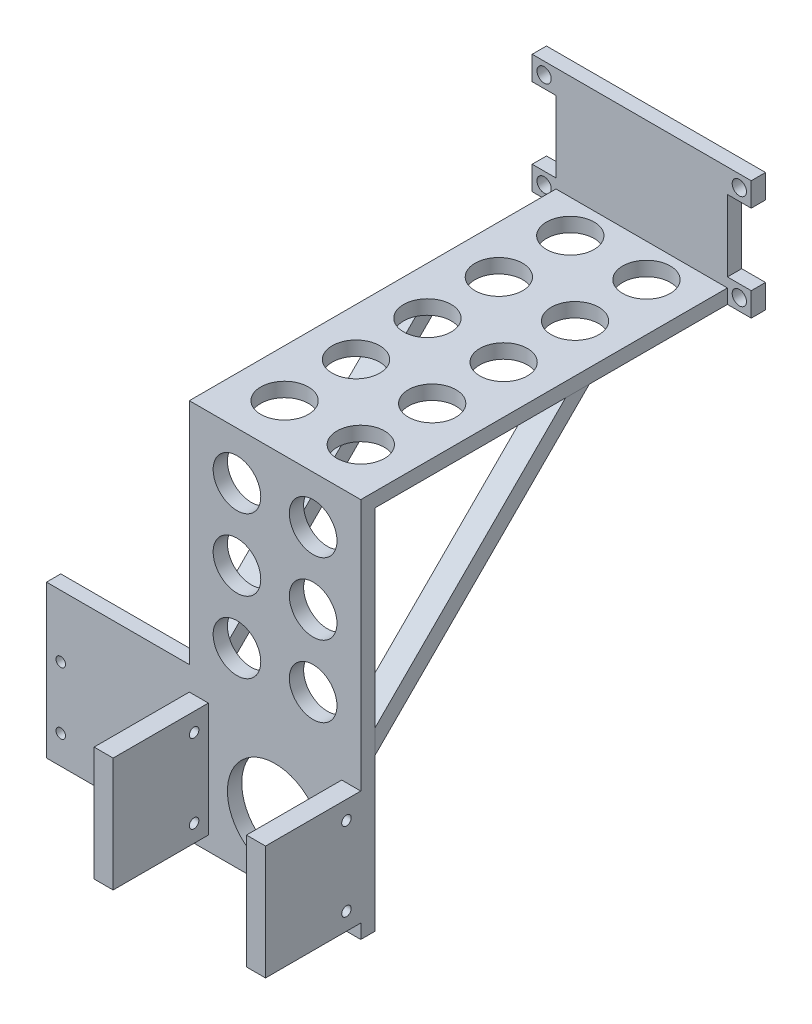
SolidWorks part; units mm, degrees
ref_plane "前视基准面" through (0, 0, 0) normal (0, 0, 1) x (1, 0, 0)
ref_plane "上视基准面" through (0, 0, 0) normal (0, 1, 0) x (1, 0, 0)
ref_plane "右视基准面" through (0, 0, 0) normal (1, 0, 0) x (0, 0, -1)
other "Configuration Table"
sketch "草图1" plane through (0, 0, 0) normal (0, 0, 1) x (1, 0, 0)
  line L1 (-18, 12.5) -> (18, 12.5)
  line L2 (-18, 12.5) -> (-18, -12.5)
  line L3 (-18, -12.5) -> (18, -12.5)
  line L4 (18, 12.5) -> (18, -12.5)
  line L5 (0, -12.5) -> (0, 12.5) construction
  line L6 (-18, 0) -> (18, 0) construction
  point P0 (0, 0)
  dimension "D1" = 25
  dimension "D2" = 36
extrude "凸台-拉伸1" add sketch "草图1" along normal blind 3
sketch "草图2" plane through (0, 0, 3) normal (0, 0, 1) x (1, 0, 0)
  line L0 (18, -12.5) -> (18, 12.5) construction
  line L1 (-18, -12.5) -> (18, -12.5)
  line L2 (-18, -12.5) -> (-18, -9.5)
  line L3 (-18, -9.5) -> (18, -9.5)
  line L4 (18, -12.5) -> (18, -9.5)
  dimension "D1" = 3
extrude "凸台-拉伸2" add sketch "草图2" along normal blind 77
sketch "草图3" plane through (0, -12.5, 0) normal (0, -1, 0) x (1, 0, 0)
  line L0 (18, 80) -> (18, 0) construction
  line L1 (-18, 80) -> (18, 80)
  line L2 (-18, 80) -> (-18, 77)
  line L3 (-18, 77) -> (18, 77)
  line L4 (18, 80) -> (18, 77)
  dimension "D1" = 3
extrude "凸台-拉伸3" add sketch "草图3" along normal blind 77
sketch "草图4" plane through (0, 0, 80) normal (0, 0, 1) x (1, 0, 0)
  line L0 (18, -89.5) -> (-18, -89.5) construction
  line L1 (18, -89.5) -> (18, -9.5) construction
  line L2 (-14, -62.5) -> (14, -62.5) construction
  line L3 (14, -62.5) -> (14, -86.5) construction
  line L4 (14, -86.5) -> (-14, -86.5) construction
  line L5 (-14, -86.5) -> (-14, -62.5) construction
  line L6 (0, -76.5) -> (-30.8667, -76.5) construction
  line L7 (-18, -9.5) -> (-18, -89.5) construction
  line L8 (-14, -62.5) -> (-18, -62.5)
  line L9 (-14, -62.5) -> (-14, -86.5)
  line L10 (-14, -86.5) -> (-18, -86.5)
  line L11 (-18, -62.5) -> (-18, -86.5)
  line L13 (18, -86.5) -> (14, -86.5)
  line L14 (18, -86.5) -> (18, -62.5)
  line L15 (18, -62.5) -> (14, -62.5)
  line L16 (14, -86.5) -> (14, -62.5)
  circle A0 centre (0, -76.5) radius 10
  dimension "D2" = 20
  dimension "D1" = 13
  dimension "D3" = 18
  dimension "D4" = 14
  dimension "D5" = 10
  dimension "D6" = 28
  dimension "D7" = 14
extrude "切除-拉伸1" cut sketch "草图4" against normal blind 77 contours A0
sketch "草图8" plane through (0, 0, 80) normal (0, 0, 1) x (1, 0, 0)
  line L0 (-14, -62.5) -> (14, -62.5) construction
  line L1 (14, -86.5) -> (-14, -86.5) construction
  line L2 (-14, -86.5) -> (-14, -62.5) construction
  line L3 (14, -62.5) -> (14, -86.5) construction
  line L4 (18, -89.5) -> (18, -9.5) construction
  line L5 (14, -62.5) -> (18, -62.5)
  line L6 (14, -62.5) -> (14, -86.5)
  line L7 (14, -86.5) -> (18, -86.5)
  line L8 (18, -62.5) -> (18, -86.5)
  line L9 (-18, -9.5) -> (-18, -89.5) construction
  line L10 (-14, -62.5) -> (-18, -62.5)
  line L11 (-14, -62.5) -> (-14, -86.5)
  line L12 (-14, -86.5) -> (-18, -86.5)
  line L13 (-18, -62.5) -> (-18, -86.5)
  circle A0 centre (0, -76.5) radius 10 construction
  circle A1 centre (0, -76.5) radius 10 construction
  dimension "D1" = 24
  dimension "D2" = 14
  dimension "D3" = 28
  dimension "D4" = 14
extrude "凸台-拉伸4" add sketch "草图8" along normal blind 20
sketch "草图9" plane through (-18, 0, 0) normal (-1, 0, 0) x (0, 0, 1)
  line L0 (100, -86.5) -> (80, -86.5) construction
  line L1 (80, -86.5) -> (80, -89.5) construction
  line L2 (100, -62.5) -> (80, -62.5) construction
  line L3 (80, -9.5) -> (80, -62.5) construction
  circle A0 centre (83, -82.85) radius 1
  circle A1 centre (83, -66.35) radius 1
  dimension "D3" = 2
  dimension "D4" = 2
  dimension "D5" = 3.85
  dimension "D1" = 3.65
  dimension "D2" = 3
  dimension "D6" = 3
sketch "草图12" plane through (18, 0, 0) normal (1, 0, 0) x (0, 0, -1)
  line L0 (0, -12.5) -> (0, 12.5) construction
  line L1 (-3, 12.5) -> (0, 12.5)
  line L2 (-3, 12.5) -> (-3, 7.5)
  line L3 (-3, 7.5) -> (0, 7.5)
  line L4 (0, 12.5) -> (0, 7.5)
  line L5 (-3, -9.5) -> (-3, 12.5) construction
  line L6 (0, -12.5) -> (-3, -12.5)
  line L7 (0, -12.5) -> (0, -7.5)
  line L8 (0, -7.5) -> (-3, -7.5)
  line L9 (-3, -12.5) -> (-3, -7.5)
  dimension "D1" = 5
  dimension "D2" = 5
extrude "凸台-拉伸5" add sketch "草图12" along normal blind 5
sketch "草图13" plane through (-18, 0, 0) normal (-1, 0, 0) x (0, 0, 1)
  line L0 (3, 12.5) -> (3, -9.5) construction
  line L1 (0, 12.5) -> (3, 12.5)
  line L2 (0, 12.5) -> (0, 7.5)
  line L3 (0, 7.5) -> (3, 7.5)
  line L4 (3, 12.5) -> (3, 7.5)
  line L5 (77, -12.5) -> (0, -12.5) construction
  line L6 (3, -12.5) -> (0, -12.5)
  line L7 (3, -12.5) -> (3, -7.5)
  line L8 (3, -7.5) -> (0, -7.5)
  line L9 (0, -12.5) -> (0, -7.5)
  line L10 (0, 12.5) -> (0, -12.5) construction
  dimension "D1" = 5
  dimension "D2" = 5
extrude "凸台-拉伸6" add sketch "草图13" along normal blind 5
sketch "草图14" plane through (0, 0, 3) normal (0, 0, 1) x (1, 0, 0)
  line L0 (-23, 7.5) -> (-18, 7.5) construction
  line L2 (-23, 7.5) -> (-23, 12.5) construction
  line L3 (0, 0) -> (0, 11.5934) construction
  line L4 (0, 0) -> (-20.8078, 0) construction
  circle A0 centre (-20.5, 10) radius 1.5
  circle A1 centre (20.5, 10) radius 1.5
  circle A2 centre (20.5, -10) radius 1.5
  circle A3 centre (-20.5, -10) radius 1.5
  dimension "D3" = 3
  dimension "D1" = 2.5
  dimension "D2" = 2.5
extrude "切除-拉伸4" cut sketch "草图14" against normal through all
sketch "草图15" plane through (-18, 0, 0) normal (-1, 0, 0) x (0, 0, 1)
  line L0 (77, -52.5) -> (37, -12.5)
  line L1 (77, -89.5) -> (77, -12.5) construction
  line L2 (77, -12.5) -> (3, -12.5) construction
  line L3 (77, -57.5) -> (32, -12.5)
  line L4 (32, -12.5) -> (37, -12.5)
  line L5 (77, -52.5) -> (77, -57.5)
  dimension "D1" = 40
  dimension "D2" = 40
  dimension "D3" = 5
extrude "凸台-拉伸7" add sketch "草图15" against normal blind 5
sketch "草图16" plane through (18, 0, 0) normal (1, 0, 0) x (0, 0, -1)
  line L0 (-77, -52.5) -> (-77, -57.5)
  line L1 (-32, -12.5) -> (-77, -57.5) construction
  line L6 (-32, -12.5) -> (-77, -57.5)
  line L7 (-77, -52.5) -> (-37, -12.5) construction
  line L8 (-77, -52.5) -> (-37, -12.5)
  line L9 (-37, -12.5) -> (-32, -12.5)
extrude "凸台-拉伸8" add sketch "草图16" against normal blind 5 separate body
extrude "切除-拉伸5" cut sketch "草图9" against normal through all
sketch "草图18" plane through (0, 0, 80) normal (0, 0, 1) x (1, 0, 0)
  line L0 (-18, -9.5) -> (-18, -62.5) construction
  line L1 (18, -62.5) -> (18, -9.5) construction
  line L2 (18, -9.5) -> (-18, -9.5) construction
  line L3 (18, -9.5) -> (-18, -9.5) construction
  circle A0 centre (-8, -19.5) radius 5
  circle A1 centre (8, -19.5) radius 5
  circle A2 centre (-8, -34.5) radius 5
  circle A3 centre (8, -34.5) radius 5
  circle A4 centre (-8, -49.5) radius 5
  circle A5 centre (8, -49.5) radius 5
  dimension "D1" = 10
  dimension "D4" = 10
  dimension "D8" = 10
  dimension "D9" = 10
  dimension "D13" = 10
  dimension "D14" = 10
  dimension "D2" = 10
  dimension "D3" = 10
  dimension "D5" = 10
  dimension "D6" = 10
  dimension "D7" = 15
  dimension "D10" = 15
  dimension "D11" = 10
  dimension "D12" = 10
  dimension "D15" = 15
  dimension "D16" = 10
  dimension "D17" = 10
  dimension "D18" = 15
extrude "切除-拉伸6" cut sketch "草图18" against normal blind 5
sketch "草图19" plane through (0, -9.5, 0) normal (0, 1, 0) x (1, 0, 0)
  line L0 (-18, -80) -> (-18, -3) construction
  line L2 (18, -80) -> (-18, -80) construction
  line L4 (18, -80) -> (18, -3) construction
  circle A0 centre (-8, -70) radius 5
  circle A1 centre (8, -70) radius 5
  circle A2 centre (-8, -55) radius 5
  circle A3 centre (8, -55) radius 5
  circle A4 centre (-8, -40) radius 5
  circle A5 centre (8, -40) radius 5
  circle A6 centre (-8, -25) radius 5
  circle A7 centre (8, -25) radius 5
  circle A8 centre (-8, -10) radius 5
  circle A9 centre (8, -10) radius 5
  dimension "D1" = 10
  dimension "D2" = 10
  dimension "D3" = 10
  dimension "D4" = 10
  dimension "D5" = 10
  dimension "D6" = 10
  dimension "D7" = 5
extrude "切除-拉伸7" cut sketch "草图19" against normal blind 5
sketch "草图20" plane through (-18, 0, 0) normal (-1, 0, 0) x (0, 0, 1)
  line L1 (80, -89.5) -> (77, -89.5)
  line L2 (80, -89.5) -> (80, -57.5)
  line L3 (80, -57.5) -> (77, -57.5)
  line L4 (77, -89.5) -> (77, -57.5)
extrude "凸台-拉伸9" add sketch "草图20" along normal blind 30
sketch "草图21" plane through (0, 0, 77) normal (0, 0, -1) x (-1, 0, 0)
  line L0 (48, -57.5) -> (48, -89.5) construction
  line L1 (47, -86.5) -> (22, -86.5) construction
  line L2 (47, -86.5) -> (47, -62.5) construction
  line L3 (47, -62.5) -> (22, -62.5) construction
  line L4 (22, -86.5) -> (22, -62.5) construction
  line L5 (48, -57.5) -> (18, -57.5) construction
  line L7 (24, -70.5) -> (45, -70.5) construction
  line L8 (24, -70.5) -> (24, -83.5) construction
  line L9 (24, -83.5) -> (45, -83.5) construction
  line L10 (45, -70.5) -> (45, -83.5) construction
  circle A0 centre (24, -70.5) radius 1
  circle A1 centre (45, -70.5) radius 1
  circle A2 centre (24, -83.5) radius 1
  circle A3 centre (45, -83.5) radius 1
  dimension "D9" = 2
  dimension "D10" = 2
  dimension "D11" = 2
  dimension "D12" = 2
  dimension "D1" = 1
  dimension "D2" = 25
  dimension "D3" = 24
  dimension "D4" = 5
  dimension "D5" = 21
  dimension "D6" = 13
  dimension "D7" = 2
  dimension "D8" = 3
extrude "切除-拉伸8" cut sketch "草图21" against normal blind 10
